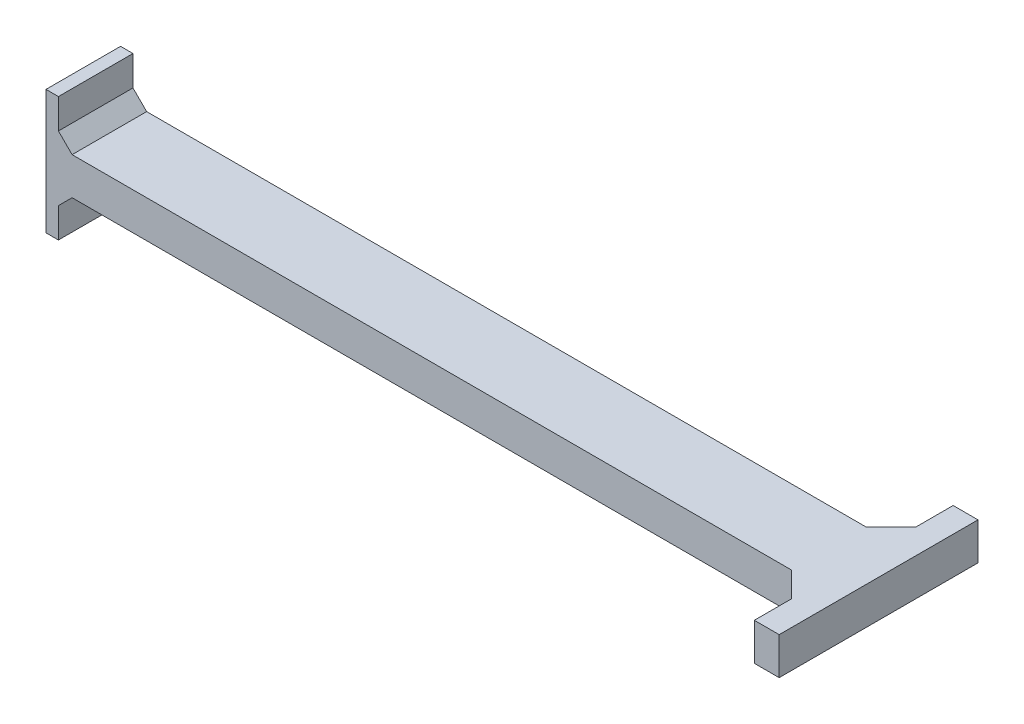
SolidWorks part; units mm, degrees
ref_plane "Front Plane" through (0, 0, 0) normal (0, 0, 1) x (1, 0, 0)
ref_plane "Top Plane" through (0, 0, 0) normal (0, 1, 0) x (1, 0, 0)
ref_plane "Right Plane" through (0, 0, 0) normal (1, 0, 0) x (0, 0, -1)
sketch "Sketch3" plane through (0, 0, 0) normal (0, 0, 1) x (1, 0, 0)
  line L0 (0, 0) -> (0, 19.05)
  line L1 (0, 19.05) -> (-367.665, 19.05)
  line L2 (-367.665, 19.05) -> (-374.65, 26.035)
  line L3 (-374.65, 26.035) -> (-374.65, 41.275)
  line L4 (-374.65, 41.275) -> (-381, 41.275)
  line L5 (-381, 41.275) -> (-381, -22.225)
  line L6 (-381, -22.225) -> (-374.65, -22.225)
  line L7 (-374.65, -22.225) -> (-374.65, -6.985)
  line L8 (-374.65, -6.985) -> (-367.665, 0)
  line L9 (-367.665, 0) -> (0, 0)
  dimension "D1" = 135
  dimension "D2" = 135
  dimension "D3" = 6.35
  dimension "D4" = 63.5
  dimension "D5" = 15.24
  dimension "D6" = 19.05
  dimension "D7" = 381
extrude "Boss-Extrude1" add sketch "Sketch3" along normal blind 38.1
sketch "Sketch4" plane through (0, 19.05, 0) normal (0, 1, 0) x (1, 0, 0)
  line L0 (0, 0) -> (12.7, 12.7)
  line L1 (12.7, 12.7) -> (12.7, 31.75)
  line L2 (12.7, 31.75) -> (25.4, 31.75)
  line L3 (25.4, 31.75) -> (25.4, -69.85)
  line L4 (25.4, -69.85) -> (12.7, -69.85)
  line L5 (12.7, -69.85) -> (12.7, -50.8)
  line L6 (12.7, -50.8) -> (0, -38.1)
  line L7 (0, 0) -> (0, -38.1)
  dimension "D1" = 135
  dimension "D2" = 101.6
  dimension "D3" = 12.7
  dimension "D4" = 19.05
extrude "Boss-Extrude2" add sketch "Sketch4" against normal up to surface (19.05 mm away) contours L3 L4 L5 L6 L7 L0 L1 L2 up to face at (-183.8325, 0, 19.05)
